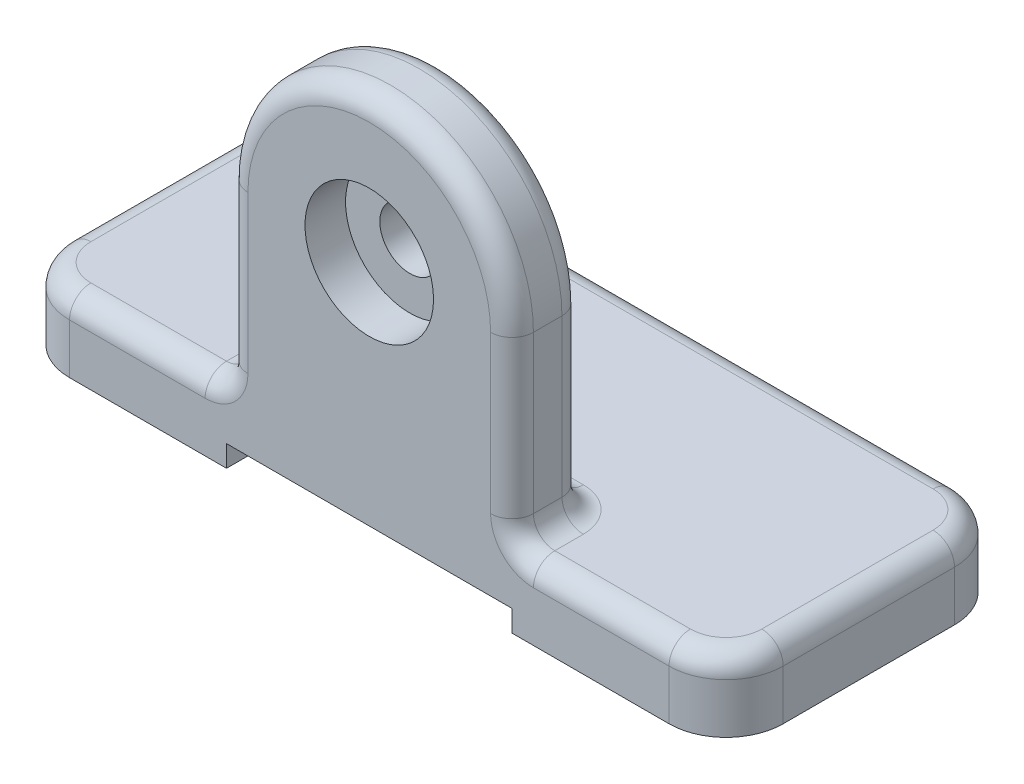
SolidWorks part; units mm, degrees
ref_plane "정면" through (0, 0, 0) normal (0, 0, 1) x (1, 0, 0)
ref_plane "윗면" through (0, 0, 0) normal (0, 1, 0) x (1, 0, 0)
ref_plane "우측면" through (0, 0, 0) normal (1, 0, 0) x (0, 0, -1)
sketch "스케치1" plane through (0, 0, 0) normal (0, 1, 0) x (1, 0, 0)
  line L1 (-50, 0) -> (50, 0)
  line L2 (-50, 0) -> (-50, 40)
  line L3 (-50, 40) -> (50, 40)
  line L4 (50, 0) -> (50, 40)
  point P4 (0, 0)
  dimension "D1" = 40
  dimension "D2" = 100
extrude "보스-돌출1" add sketch "스케치1" along normal blind 10
sketch "스케치2" plane through (0, 0, 0) normal (0, 0, 1) x (1, 0, 0)
  line L0 (-20, 0) -> (-20, 35)
  line L1 (-50, 0) -> (50, 0) construction
  line L2 (20, 35) -> (20, 0)
  line L3 (20, 0) -> (-20, 0)
  line L4 (-50, 10) -> (-50, 0) construction
  arc A0 (-20, 35) -> (20, 35) centre (0, 35) cw
  dimension "D1" = 20
  dimension "D2" = 50
  dimension "D3" = 35
extrude "보스-돌출2" add sketch "스케치2" against normal blind 10
sketch "스케치3" plane through (0, 0, 0) normal (0, 0, 1) x (1, 0, 0)
  line L0 (-50, 0) -> (50, 0) construction
  line L1 (-20, 3) -> (20, 3)
  line L2 (-20, 3) -> (-20, 0)
  line L3 (-20, 0) -> (20, 0)
  line L4 (20, 3) -> (20, 0)
  line L5 (-20, 35) -> (-20, 10) construction
  line L6 (20, 10) -> (20, 35) construction
  dimension "D1" = 3
extrude "컷-돌출1" cut sketch "스케치3" against normal through all contours L1 L4 L3 L2
hole_wizard "M8 육각 머리 볼트용 카운터보어1" positions "3D스케치1" profile "스케치4" counterbore size "M8" standard "Ansi Metric" end condition through all
sketch3d "3D스케치1"
  line L0 (0, 35, -10) -> (0, 35, 0) construction
  point P0 (0, 35, 0)
sketch "스케치4" plane through (0, 35, 0) normal (1, 0, 0) x (0, -1, 0)
  line L0 (0, 0) -> (0, 40)
  line L1 (0, 40) -> (4.2, 40)
  line L3 (4.2, 40) -> (4.2, 5.68)
  line L4 (4.2, 5.68) -> (9.005, 5.68)
  line L5 (9.005, 5.68) -> (9.005, 0)
  line L7 (9.005, 0) -> (0, 0)
  line L11 (0, -6.35) -> (0, 107.95) construction
  dimension "관통 구멍 지름" = 8.4
  dimension "관통 구멍 깊이" = 40
  dimension "카운터보어 지름" = 18.01
  dimension "카운터보어 깊이" = 5.68
fillet "필렛1" radius 8 4 edges at (-50, 5, 0) (-50, 5, -40) (50, 5, 0) (50, 5, -40)
fillet "필렛2" radius 3 18 edges at (20, 22.5, -10) (20, 22.5, 0) (-20, 22.5, 0) (-20, 22.5, -10) (0, 55, 0) (0, 55, -10) (-31, 10, 0) (-47.6569, 10, -2.3431) (-50, 10, -20) (-47.6569, 10, -37.6569) (0, 10, -40) (47.6569, 10, -37.6569) (50, 10, -20) (47.6569, 10, -2.3431) (31, 10, 0) (-20, 10, -5) (0, 10, -10) (20, 10, -5)
